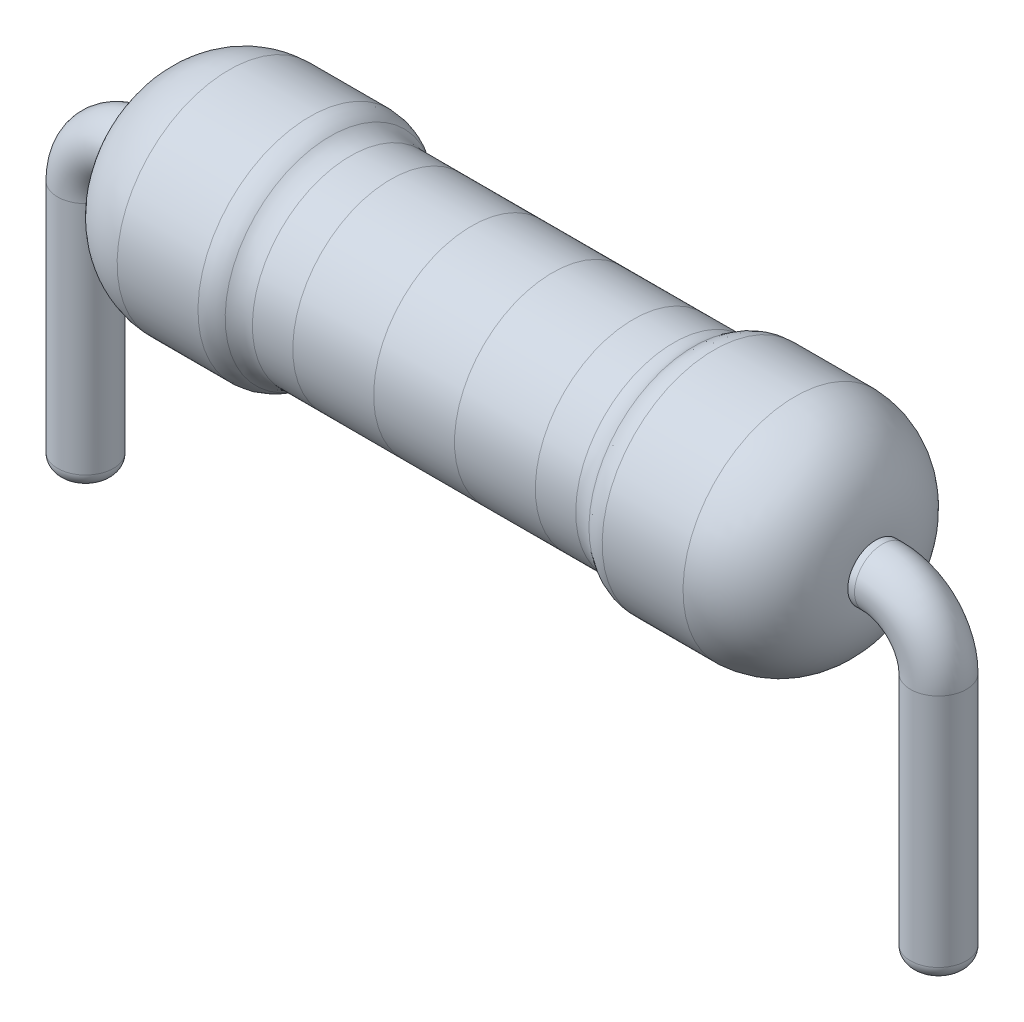
SolidWorks part; units mm, degrees
ref_plane "Alzado" through (0, 0, 0) normal (0, 0, 1) x (1, 0, 0)
ref_plane "Planta" through (0, 0, 0) normal (0, 1, 0) x (1, 0, 0)
ref_plane "Vista lateral" through (0, 0, 0) normal (1, 0, 0) x (0, 0, -1)
sketch "Croquis1" plane through (0, 0, 0) normal (0, 0, 1) x (1, 0, 0)
  line L0 (0, 38.5639) -> (0, -22.2406) construction
  line L2 (22.2406, 0) -> (-13.8748, 0) construction
  line L3 (-1.4444, 0.875) -> (1.4444, 0.875)
  line L5 (-3.25, 0) -> (3.25, 0)
  line L9 (-3.25, 0) -> (-3.25, 0.25)
  line L10 (-2.5278, 1) -> (-1.8056, 1)
  line L12 (-2.5278, 0) -> (-2.5278, 1) construction
  line L13 (-1.8056, 0) -> (-1.8056, 1) construction
  line L14 (-1.0833, 0) -> (-1.0833, 1) construction
  line L15 (-0.3611, 0) -> (-0.3611, 1) construction
  line L17 (-2.5278, 0.5) -> (-1.8056, 0.5) construction
  line L18 (-1.8056, 0.5) -> (-1.0833, 0.5) construction
  line L19 (-1.0833, 0.5) -> (-0.3611, 0.5) construction
  line L20 (-0.3611, 0.5) -> (0.3611, 0.5) construction
  line L21 (-1.4444, 0.5) -> (-1.4444, 0.875) construction
  line L22 (-2.5278, 0.5) -> (-3.25, 0.5) construction
  line L26 (2.5278, 1) -> (1.8056, 1)
  line L27 (3.25, 0) -> (3.25, 0.25)
  arc A9 (-2.5278, 1) -> (-3.25, 0.25) centre (-2.4995, 0.25) ccw
  arc A13 (-1.625, 0.9375) -> (-1.4444, 0.875) centre (-1.4444, 1.1671) ccw
  arc A14 (-1.625, 0.9375) -> (-1.8056, 1) centre (-1.8056, 0.7079) ccw
  arc A16 (1.625, 0.9375) -> (1.8056, 1) centre (1.8056, 0.7079) cw
  arc A17 (1.625, 0.9375) -> (1.4444, 0.875) centre (1.4444, 1.1671) cw
  arc A18 (2.5278, 1) -> (3.25, 0.25) centre (2.4995, 0.25) cw
  point P24 (0, 0.5)
  dimension "D_Max" = 2
  dimension "D_wire" = 0.5
  dimension "D_Min" = 1.75
  dimension "L" = 6.5
revolve "Revolución1" add sketch "Croquis1" angle 360 about L5
sketch "Croquis4" plane through (0, 0, 0) normal (0, 0, 1) x (1, 0, 0)
  line L0 (0, 1.6186) -> (0, -1.7093) construction
  line L1 (-2.5278, 1) -> (-2.5278, -1)
  line L2 (-1.8056, 1) -> (-1.8056, -1)
  line L3 (-1.0833, 1) -> (-1.0833, -1)
  line L4 (-0.3611, 1) -> (-0.3611, -1)
  line L5 (0.3611, 1) -> (0.3611, -1)
  line L6 (1.0833, 1) -> (1.0833, -1)
  line L7 (1.8056, 1) -> (1.8056, -1)
  line L8 (2.5278, 1) -> (2.5278, -1)
  line L10 (-2.1667, -1) -> (-2.1667, 1) construction
  line L12 (-2.5278, 0) -> (-1.8056, 0) construction
  line L13 (-1.8056, 0) -> (-1.0833, 0) construction
  line L14 (-1.0833, 0) -> (-0.3611, 0) construction
  line L15 (-0.3611, 0) -> (0.3611, 0) construction
  line L16 (-1.8056, 1) -> (-2.5278, 1) construction
  line L17 (-2.5278, -1) -> (-1.8056, -1) construction
  point P39 (0, 0)
  point P40 (-2.1667, 0)
split line "Línea de partición1"
sketch "Croquis2" plane through (0, 0, 0) normal (1, 0, 0) x (0, 0, -1)
  circle A0 centre (0, 0) radius 0.25
  circle A2 centre (0, 0) radius 0.25 construction
sketch "Croquis3" plane through (0, 0, 0) normal (0, 0, 1) x (1, 0, 0)
  line L0 (3.31, 0) -> (-3.31, 0)
  line L1 (-3.81, -0.5) -> (-3.81, -2.725)
  line L2 (0, -1.6403) -> (0, -1.2606) construction
  line L3 (3.81, -0.5) -> (3.81, -2.725)
  line L4 (-2.0924, -1) -> (-4.0105, -1) construction
  line L6 (-2.5278, -1) -> (-1.8056, -1) construction
  arc A0 (-3.31, 0) -> (-3.81, -0.5) centre (-3.31, -0.5) ccw
  arc A1 (3.31, 0) -> (3.81, -0.5) centre (3.31, -0.5) cw
  point P15 (-3.81, 0)
  dimension "Wire_curve" = 0.5
  dimension "L_Wire" = 7.62
  dimension "wire_lengthh" = 1.725
sweep "Barrer1" add profiles "Croquis2" path "Croquis3"
fillet "Redondeo1" radius 0.125 2 edges at (-3.81, -2.725, -0.25) (3.81, -2.725, -0.25)
